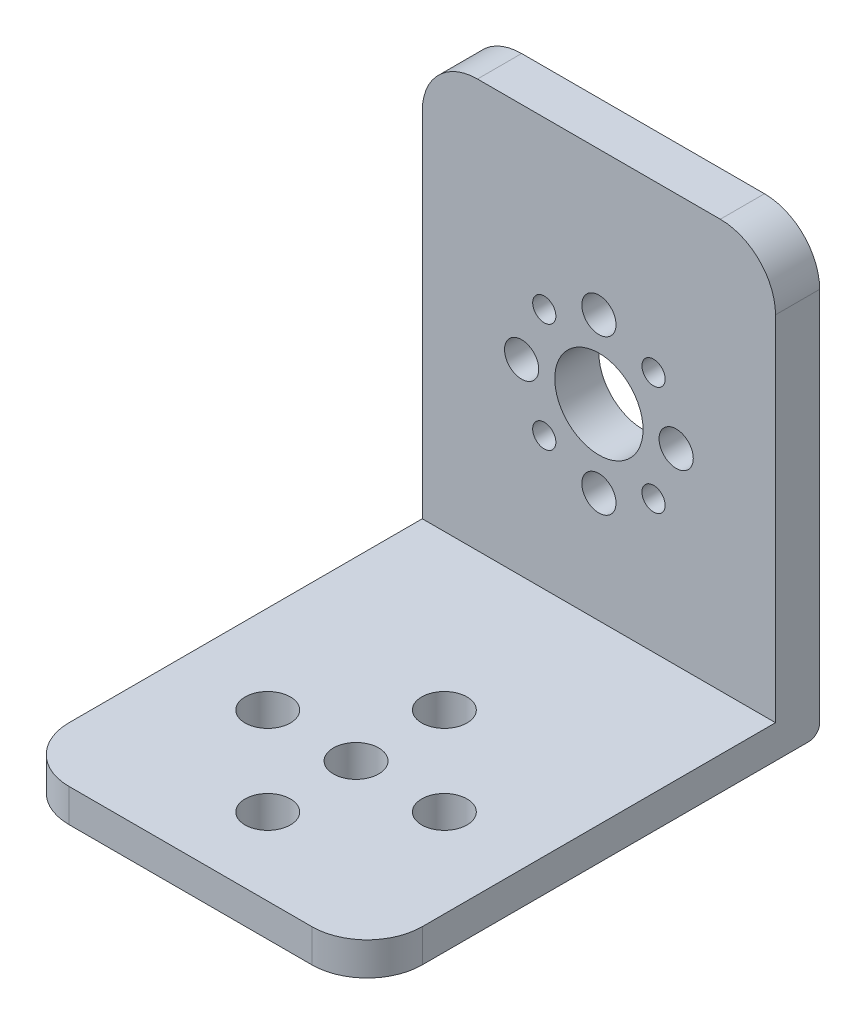
SolidWorks part; units mm, degrees
ref_plane "前视基准面" through (0, 0, 0) normal (0, 0, 1) x (1, 0, 0)
ref_plane "上视基准面" through (0, 0, 0) normal (0, 1, 0) x (1, 0, 0)
ref_plane "右视基准面" through (0, 0, 0) normal (1, 0, 0) x (0, 0, -1)
sketch "草图2" plane through (0, 0, 0) normal (0, 1, 0) x (1, 0, 0)
  line L1 (-16, 20) -> (16, 20)
  line L2 (-16, 20) -> (-16, -20)
  line L3 (-16, -20) -> (16, -20)
  line L4 (16, 20) -> (16, -20)
  line L5 (-16, 20) -> (16, -20) construction
  line L6 (-16, -20) -> (16, 20) construction
  point P0 (0, 0)
  dimension "D1" = 32
  dimension "D2" = 40
extrude "凸台-拉伸1" add sketch "草图2" along normal blind 3
sketch "草图3" plane through (0, 3, 0) normal (0, 1, 0) x (1, 0, 0)
  line L0 (-16, 17) -> (16, 17)
  line L1 (-16, 20) -> (-16, -20) construction
  line L2 (16, -20) -> (16, 20) construction
  line L3 (16, 17) -> (16, 20)
  line L4 (16, 20) -> (-16, 20)
  line L5 (-16, 20) -> (-16, 17)
  dimension "D1" = 3
extrude "凸台-拉伸2" add sketch "草图3" along normal blind 37
sketch "草图4" plane through (0, 0, -17) normal (0, 0, 1) x (1, 0, 0)
  line L0 (0, 0) -> (0, 40) construction
  line L1 (-16, 40) -> (16, 40) construction
  line L2 (0, 20) -> (27.0067, 20) construction
  line L3 (0, 20) -> (9.8715, 29.8715) construction
  circle A0 centre (0, 20) radius 4
  circle A1 centre (7, 20) radius 1.55
  circle A2 centre (0, 13) radius 1.55
  circle A3 centre (-7, 20) radius 1.55
  circle A4 centre (0, 27) radius 1.55
  circle A5 centre (4.9497, 24.9497) radius 1.05
  circle A6 centre (4.9497, 15.0503) radius 1.05
  circle A7 centre (-4.9497, 15.0503) radius 1.05
  circle A8 centre (-4.9497, 24.9497) radius 1.05
  point P19 (0, 20)
  point P29 (0, 20)
  dimension "D1" = 7
  dimension "D3" = 3.1
  dimension "D4" = 8
  dimension "D6" = 2.1
  dimension "D7" = 7
  dimension "D5" = 45
  dimension "D2" = 4
  dimension "D8" = 4
extrude "切除-拉伸1" cut sketch "草图4" against normal through all
sketch "草图6" plane through (0, 3, 0) normal (0, 1, 0) x (1, 0, 0)
  line L0 (-16, -5) -> (36.5581, -5) construction
  line L1 (-16, 17) -> (-16, -20) construction
  line L2 (16, 20) -> (-16, 20) construction
  line L3 (0, 0) -> (0, -31.2484) construction
  circle A0 centre (0, -5) radius 2.05
  circle A1 centre (-8, -5) radius 2.05
  circle A2 centre (8, -5) radius 2.05
  circle A3 centre (0, 3) radius 2.05
  circle A4 centre (0, -13) radius 2.05
  dimension "D2" = 4.1
  dimension "D3" = 4.1
  dimension "D4" = 4.1
  dimension "D5" = 8
  dimension "D6" = 8
  dimension "D7" = 4.1
  dimension "D8" = 4.1
  dimension "D9" = 8
  dimension "D10" = 8
  dimension "D1" = 25
extrude "切除-拉伸2" cut sketch "草图6" against normal through all
fillet "圆角1" radius 5 4 edges at (16, 40, -18.5) (-16, 40, -18.5) (-16, 1.5, 20) (16, 1.5, 20)
sketch "草图11" plane through (0, 0, -20) normal (0, 0, -1) x (-1, 0, 0)
  line L4 (11, 40) -> (-11, 40)
  line L5 (-16, 35) -> (-16, 0)
  line L6 (-16, 0) -> (16, 0)
  line L7 (16, 0) -> (16, 35)
  line L8 (11, 40) -> (-11, 40)
  line L9 (-16, 35) -> (-16, 0)
  line L10 (-16, 0) -> (16, 0)
  line L11 (16, 0) -> (16, 35)
  circle A0 centre (-7, 20) radius 1.55 construction
  circle A1 centre (-4.9497, 15.0503) radius 1.05 construction
  arc A2 (-11, 40) -> (-16, 35) centre (-11, 35) ccw
  arc A3 (16, 35) -> (11, 40) centre (11, 35) ccw
  arc A4 (-11, 40) -> (-16, 35) centre (-11, 35) ccw
  arc A5 (16, 35) -> (11, 40) centre (11, 35) ccw
  circle A6 centre (0, 13) radius 1.55 construction
  circle A7 centre (0, 20) radius 4 construction
  circle A8 centre (4.9497, 15.0503) radius 1.05 construction
  circle A9 centre (7, 20) radius 1.55 construction
  circle A10 centre (4.9497, 24.9497) radius 1.05 construction
  circle A11 centre (-4.9497, 24.9497) radius 1.05 construction
  circle A12 centre (0, 27) radius 1.55 construction
  circle A13 centre (-7, 20) radius 1.55
  circle A14 centre (-4.9497, 15.0503) radius 1.05
  circle A15 centre (0, 13) radius 1.55
  circle A16 centre (0, 20) radius 4
  circle A17 centre (4.9497, 15.0503) radius 1.05
  circle A18 centre (7, 20) radius 1.55
  circle A19 centre (4.9497, 24.9497) radius 1.05
  circle A20 centre (-4.9497, 24.9497) radius 1.05
  circle A21 centre (0, 27) radius 1.55
  dimension "D1" = 0
extrude "凸台-拉伸4" add sketch "草图11" along normal blind 1
fillet "圆角3" radius 1 1 edges at (0, 0, -21)
